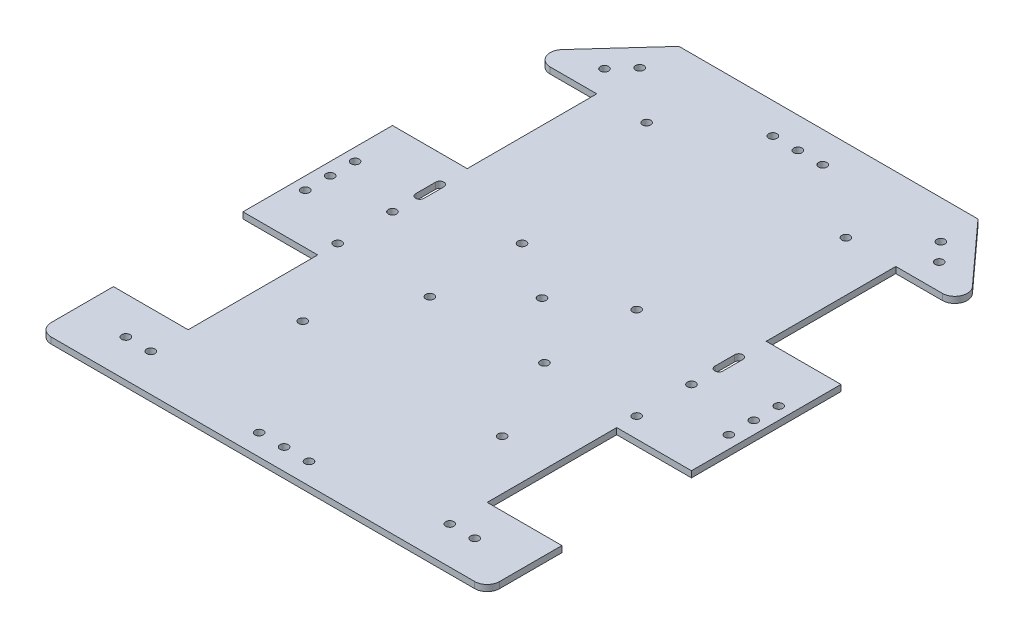
SolidWorks part; units mm, degrees
ref_plane "Front Plane" through (0, 0, 0) normal (0, 0, 1) x (1, 0, 0)
ref_plane "Top Plane" through (0, 0, 0) normal (0, 1, 0) x (1, 0, 0)
ref_plane "Right Plane" through (0, 0, 0) normal (1, 0, 0) x (0, 0, -1)
sketch "Sketch1" plane through (0, 0, 0) normal (0, 1, 0) x (1, 0, 0)
  line L0 (0, 0) -> (0, 60)
  line L1 (0, 60) -> (30, 60)
  line L2 (30, 60) -> (30, 112)
  line L3 (30, 112) -> (0, 112)
  line L4 (0, 112) -> (30, 145)
  line L5 (0, 0) -> (30, 0)
  line L6 (30, 0) -> (30, -52)
  line L7 (30, -52) -> (0, -52)
  line L8 (0, -52) -> (0, -82)
  line L9 (30, 145) -> (150, 145)
  line L10 (0, -82) -> (180, -82)
  line L11 (90, 145) -> (90, -82) construction
  line L12 (180, -52) -> (180, -82)
  line L13 (150, -52) -> (180, -52)
  line L14 (150, 0) -> (150, -52)
  line L15 (180, 0) -> (150, 0)
  line L16 (180, 0) -> (180, 60)
  line L17 (180, 60) -> (150, 60)
  line L18 (150, 60) -> (150, 112)
  line L19 (150, 112) -> (180, 112)
  line L20 (180, 112) -> (150, 145)
  dimension "D1" = 60
  dimension "D2" = 30
  dimension "D3" = 52
  dimension "D4" = 33
  dimension "D5" = 52
  dimension "D6" = 30
  dimension "D7" = 60
  dimension "D8" = 90
extrude "Boss-Extrude1" add sketch "Sketch1" along normal blind 2.5
fillet "Fillet1" radius 5 2 edges at (180, 1.25, 82) (0, 1.25, 82)
fillet "Fillet2" radius 5 2 edges at (0, 1.25, -112) (180, 1.25, -112)
sketch "Sketch2" plane through (0, 2.5, 0) normal (0, 1, 0) x (1, 0, 0)
  line L0 (30, 60) -> (30, 30) construction
  line L1 (30, 41) -> (30, 49) construction
  line L2 (28.35, 41) -> (28.35, 49)
  line L3 (31.65, 41) -> (31.65, 49)
  line L4 (30, -52) -> (30, -82) construction
  line L5 (5, -82) -> (175, -82) construction
  line L6 (30, 112) -> (50, 112) construction
  line L7 (90, 145) -> (90, -82) construction
  line L8 (150, 145) -> (30, 145) construction
  line L9 (150, 41) -> (150, 49) construction
  line L10 (151.65, 41) -> (151.65, 49)
  line L11 (148.35, 41) -> (148.35, 49)
  circle A0 centre (30, 30) radius 1.65
  arc A1 (28.35, 41) -> (31.65, 41) centre (30, 41) ccw
  arc A2 (31.65, 49) -> (28.35, 49) centre (30, 49) ccw
  circle A3 centre (30, -67) radius 1.65
  circle A4 centre (50, 112) radius 1.65
  circle A5 centre (50, -26) radius 1.65
  circle A6 centre (150, -67) radius 1.65
  circle A7 centre (130, -26) radius 1.65
  arc A8 (151.65, 41) -> (148.35, 41) centre (150, 41) cw
  arc A9 (148.35, 49) -> (151.65, 49) centre (150, 49) cw
  circle A10 centre (150, 30) radius 1.65
  circle A11 centre (130, 112) radius 1.65
  circle A12 centre (20, -67) radius 1.65
  circle A13 centre (160, -67) radius 1.65
  point P6 (30, 45)
  point P34 (150, 45)
  dimension "D1" = 3.3
  dimension "D4" = 3.3
  dimension "D6" = 3.3
  dimension "D7" = 3.3
  dimension "D8" = 3.3
  dimension "D2" = 3.3
  dimension "D3" = 8
  dimension "D5" = 20
  dimension "D9" = 10
extrude "Cut-Extrude1" cut sketch "Sketch2" against normal through all
sketch "Sketch3" plane through (0, 2.5, 0) normal (0, 1, 0) x (1, 0, 0)
  line L0 (18.8015, 132.6817) -> (161.1985, 132.6817) construction
  line L1 (30, 145) -> (7.6031, 120.3634) construction
  line L2 (172.3969, 120.3634) -> (150, 145) construction
  line L4 (150, 145) -> (30, 145) construction
  line L5 (90, 145) -> (90, 132.6817) construction
  circle A0 centre (90, 132.6817) radius 1.65
  circle A1 centre (80, 132.6817) radius 1.65
  circle A2 centre (100, 132.6817) radius 1.65
  point P13 (0, 0)
  dimension "D2" = 3.3
  dimension "D3" = 3.3
  dimension "D1" = 10
extrude "Cut-Extrude2" cut sketch "Sketch3" against normal blind 10
sketch "Sketch4" plane through (0, 2.5, 0) normal (0, 1, 0) x (1, 0, 0)
  line L0 (0, -73.5004) -> (180, -73.5004) construction
  line L1 (0, -52) -> (0, -77) construction
  line L2 (180, -77) -> (180, -52) construction
  line L3 (90, -73.5004) -> (90, -82) construction
  line L4 (5, -82) -> (175, -82) construction
  circle A0 centre (90, -73.5004) radius 1.65
  circle A1 centre (80, -73.5004) radius 1.65
  circle A2 centre (100, -73.5004) radius 1.65
  dimension "D1" = 3.3
  dimension "D2" = 3.3
  dimension "D3" = 10
extrude "Cut-Extrude3" cut sketch "Sketch4" against normal blind 10
sketch "Sketch5" plane through (0, 2.5, 0) normal (0, 1, 0) x (1, 0, 0)
  line L0 (5, 60) -> (5, 0) construction
  line L1 (30, 60) -> (0, 60) construction
  line L2 (0, 0) -> (30, 0) construction
  line L3 (0, 60) -> (0, 0) construction
  line L4 (90, 145) -> (90, -82) construction
  line L5 (150, 145) -> (30, 145) construction
  line L6 (5, -82) -> (175, -82) construction
  circle A0 centre (5, 30) radius 1.65
  circle A1 centre (5, 40) radius 1.65
  circle A2 centre (5, 20) radius 1.65
  circle A3 centre (175, 20) radius 1.65
  circle A4 centre (175, 30) radius 1.65
  circle A5 centre (175, 40) radius 1.65
  dimension "D2" = 3.3
  dimension "D3" = 3.3
  dimension "D5" = 3.3
  dimension "D1" = 5
  dimension "D4" = 10
  dimension "D6" = 10
extrude "Cut-Extrude4" cut sketch "Sketch5" against normal blind 10
sketch "Sketch6" plane through (0, 2.5, 0) normal (0, 1, 0) x (1, 0, 0)
  line L0 (0, 30) -> (180, 30) construction
  line L1 (0, 60) -> (0, 0) construction
  line L2 (180, 0) -> (180, 60) construction
  circle A0 centre (90, 30) radius 1.65
  dimension "D1" = 3.3
extrude "Cut-Extrude5" cut sketch "Sketch6" against normal blind 10
sketch "Sketch8" plane through (0, 2.5, 0) normal (0, 1, 0) x (1, 0, 0)
  line L0 (18.8015, 132.6817) -> (26.2009, 125.955) construction
  line L2 (30, 145) -> (7.6031, 120.3634) construction
  line L3 (8.8873, 106.9099) -> (43.5146, 145) construction
  line L4 (150, 145) -> (30, 145) construction
  line L5 (90, 145) -> (90, 111.2816) construction
  circle A0 centre (29.5643, 129.6547) radius 1.65
  circle A1 centre (22.8376, 122.2553) radius 1.65
  circle A2 centre (157.1624, 122.2553) radius 1.65
  circle A3 centre (150.4357, 129.6547) radius 1.65
  point P10 (26.2009, 125.955)
  dimension "D2" = 3.3
  dimension "D3" = 3.3
  dimension "D1" = 10
  dimension "D4" = 5
  dimension "D5" = 5
extrude "Cut-Extrude6" cut sketch "Sketch8" against normal blind 10
sketch "Sketch9" plane through (0, 2.5, 0) normal (0, 1, 0) x (1, 0, 0)
  line L0 (30, 44.9967) -> (30, 7.9967) construction
  line L1 (90, 30) -> (90, 20.3634) construction
  circle A0 centre (30, 7.9967) radius 1.65
  circle A1 centre (67, 44.9967) radius 1.65
  circle A2 centre (67, 7.9967) radius 1.65
  circle A3 centre (150, 7.9967) radius 1.65
  circle A4 centre (113, 7.9967) radius 1.65
  circle A5 centre (113, 44.9967) radius 1.65
  dimension "D4" = 3.3
  dimension "D1" = 37
  dimension "D2" = 37
  dimension "D3" = 37
extrude "Cut-Extrude7" cut sketch "Sketch9" against normal blind 10
